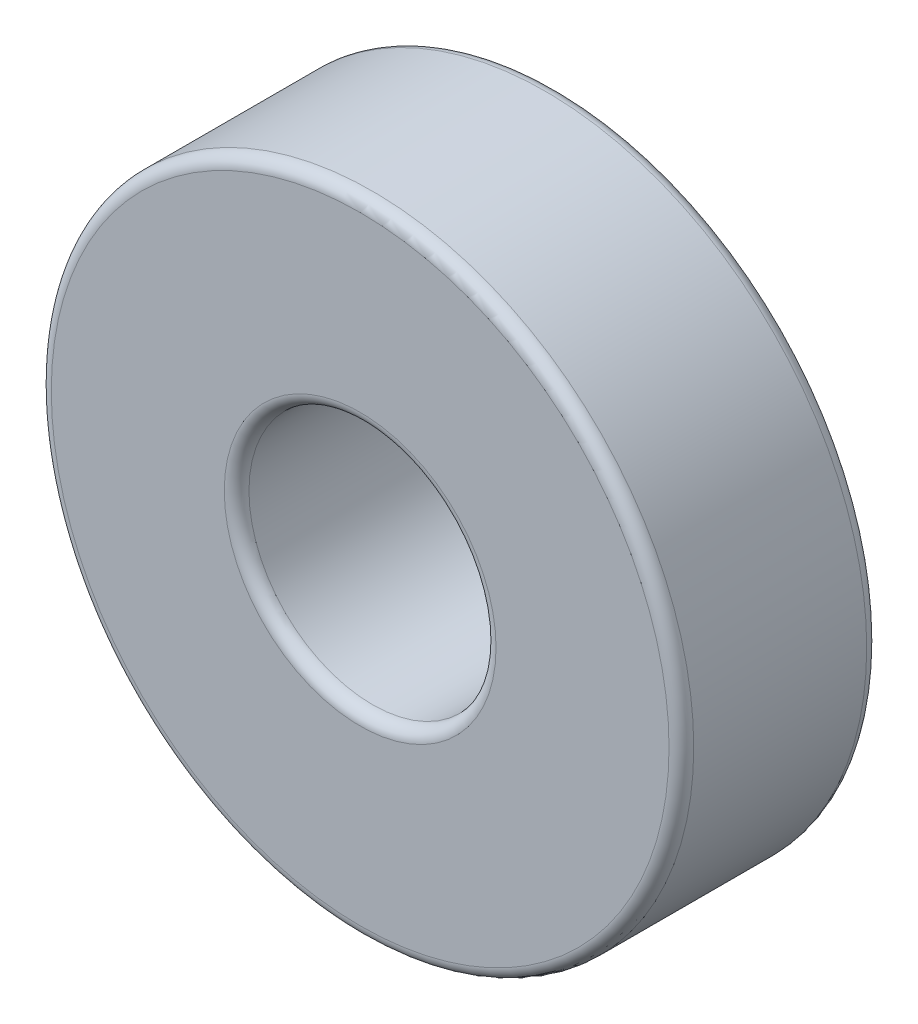
SolidWorks part; units mm, degrees
ref_plane "Alzado" through (0, 0, 0) normal (0, 0, 1) x (1, 0, 0)
ref_plane "Planta" through (0, 0, 0) normal (0, 1, 0) x (1, 0, 0)
ref_plane "Vista lateral" through (0, 0, 0) normal (1, 0, 0) x (0, 0, -1)
sketch "Croquis1" plane through (0, 0, 0) normal (0, 0, 1) x (1, 0, 0)
  circle A0 centre (0, 0) radius 5
  circle A1 centre (0, 0) radius 13
  dimension "D1" = 10
  dimension "D2" = 26
extrude "Saliente-Extruir1" add sketch "Croquis1" along normal blind 8
fillet "Redondeo1" radius 0.5 4 edges at (5, 0, 8) (5, 0, 0) (13, 0, 0) (13, 0, 8)
